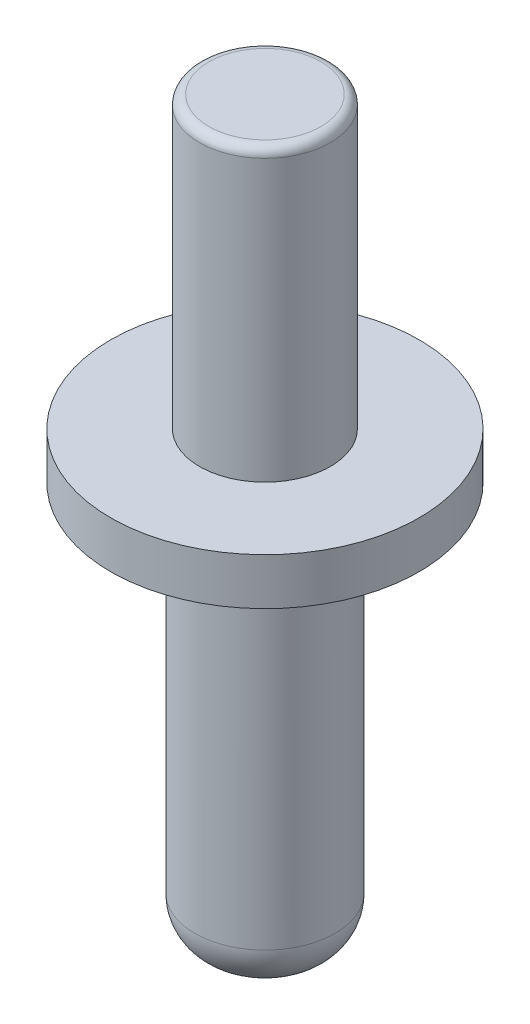
SolidWorks part; units mm, degrees
ref_plane "前视基准面" through (0, 0, 0) normal (0, 0, 1) x (1, 0, 0)
ref_plane "上视基准面" through (0, 0, 0) normal (0, 1, 0) x (1, 0, 0)
ref_plane "右视基准面" through (0, 0, 0) normal (1, 0, 0) x (0, 0, -1)
sketch "草图1" plane through (0, 0, 0) normal (0, 0, 1) x (1, 0, 0)
  line L0 (0, 16.2872) -> (0, -9.0872) construction
  line L1 (0, -4.3) -> (-0.75, -4.3)
  line L2 (-0.75, -4.3) -> (-0.75, 0)
  line L3 (-0.75, 0) -> (-1.65, 0)
  line L4 (-1.65, 0) -> (-1.65, 0.5)
  line L5 (-1.65, 0.5) -> (-0.7, 0.5)
  line L6 (-0.7, 0.5) -> (-0.7, 3.6)
  line L7 (-0.7, 3.6) -> (0, 3.6)
  line L8 (0, -4.3) -> (0, 3.6)
  line L12 (5.0295, 0) -> (-9.301, 0) construction
  point P23 (-1.65, 0.25)
  dimension "D1" = 7.9
  dimension "D2" = 0.5
  dimension "D3" = 0.7
  dimension "D4" = 3.1
  dimension "D5" = 0.75
  dimension "D6" = 1.65
revolve "旋转1" add sketch "草图1" angle 360 about L0
fillet "圆角1" radius 0.1 1 edges at (-0.7, 3.6, 0)
fillet "圆角2" radius 0.5 1 edges at (-0.75, -4.3, 0)
